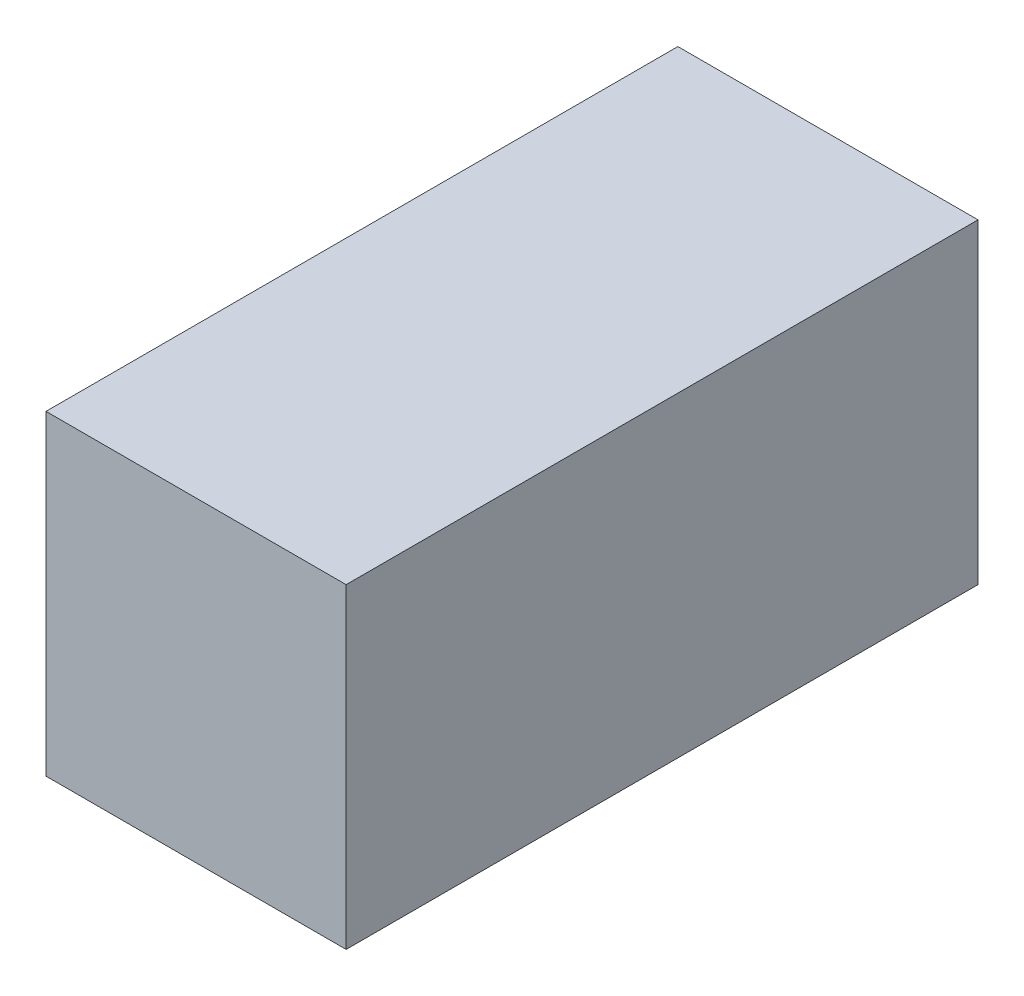
SolidWorks part; units mm, degrees
ref_plane "Front Plane" through (0, 0, 0) normal (0, 0, 1) x (1, 0, 0)
ref_plane "Top Plane" through (0, 0, 0) normal (0, 1, 0) x (1, 0, 0)
ref_plane "Right Plane" through (0, 0, 0) normal (1, 0, 0) x (0, 0, -1)
sketch "Sketch1" plane through (0, 0, 0) normal (1, 0, 0) x (0, 0, -1)
  line L1 (0, 0) -> (40, 0)
  line L2 (0, 0) -> (0, 20)
  line L3 (0, 20) -> (40, 20)
  line L4 (40, 0) -> (40, 20)
extrude "Boss-Extrude1" add sketch "Sketch1" against normal blind 19
